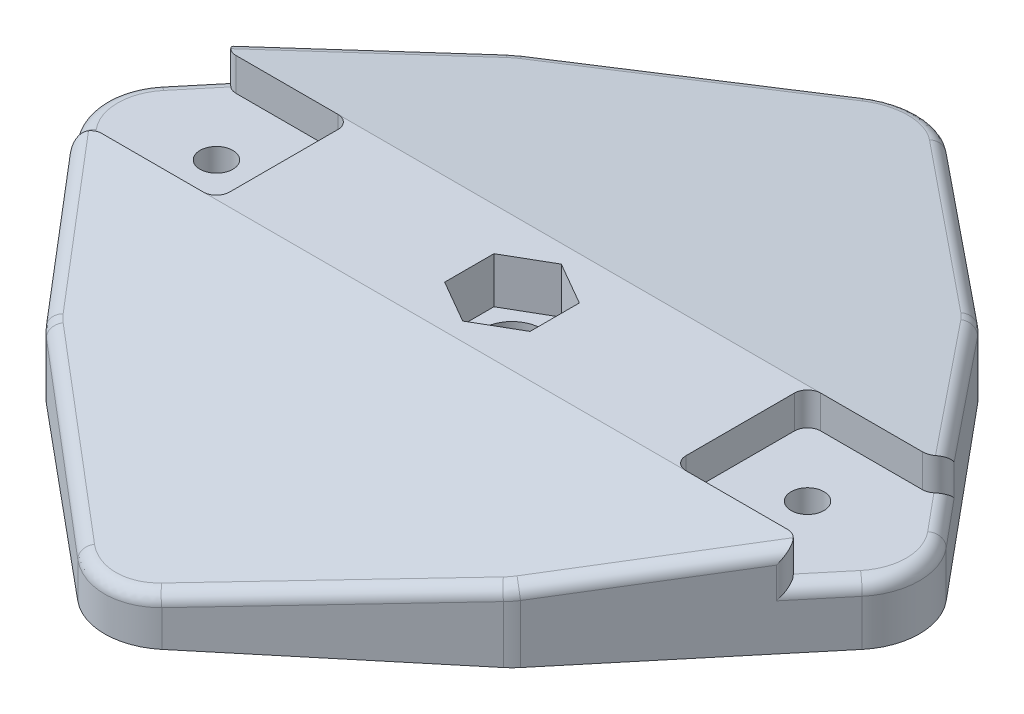
SolidWorks part; units mm, degrees
ref_plane "Front" through (0, 0, 0) normal (0, 0, 1) x (1, 0, 0)
ref_plane "Top" through (0, 0, 0) normal (0, 1, 0) x (1, 0, 0)
ref_plane "Right" through (0, 0, 0) normal (1, 0, 0) x (0, 0, -1)
sketch "Esquisse1" plane through (0, 0, 0) normal (0, 1, 0) x (1, 0, 0)
  line L0 (-45, 0) -> (45, 0) construction
  line L5 (-65.0329, 0) -> (0, -78.1935)
  line L6 (-65.0329, 0) -> (0, 78.1935)
  line L7 (0, -78.1935) -> (65.0329, 0)
  line L8 (0, 78.1935) -> (65.0329, 0)
  circle A0 centre (0, 0) radius 4.5
  circle A1 centre (-45, 0) radius 2.5
  circle A2 centre (45, 0) radius 2.5
  point P48 (0, 0)
  dimension "D1" = 9
  dimension "D3" = 5
  dimension "D5" = 100
  dimension "D2" = 100
  dimension "D4" = 90
  dimension "D6" = 100.5
extrude "Boss.-Extru.1" add sketch "Esquisse1" along normal blind 9
sketch "Esquisse2" plane through (0, 9, 0) normal (0, 1, 0) x (1, 0, 0)
  line L0 (0, 65.0329) -> (-78.1935, 0)
  line L1 (-78.1935, 0) -> (0, -65.0329)
  line L2 (0, -65.0329) -> (78.1935, 0)
  line L3 (78.1935, 0) -> (0, 65.0329)
  line L4 (-78.1935, 0) -> (78.1935, 0) construction
  line L5 (65.0329, 0) -> (0, 78.1935) construction
  dimension "D1" = 100.5
extrude "Enlèv. mat.-Extru.1" cut sketch "Esquisse2" against normal through all flip side to cut
fillet "Congé1" radius 10 8 edges at (0, 4.5, 65.0329) (-35.5043, 4.5, 35.5043) (-35.5043, 4.5, -35.5043) (0, 4.5, -65.0329) (35.5043, 4.5, -35.5043) (65.0329, 4.5, 0) (35.5043, 4.5, 35.5043) (-65.0329, 4.5, 0)
sketch "Esquisse3" plane through (0, 9, 0) normal (0, 1, 0) x (1, 0, 0)
  line L0 (0, -50) -> (0, 50) construction
  line L1 (-56.508, 10.25) -> (-34.75, 10.25)
  line L3 (-56.508, -10.25) -> (-34.75, -10.25)
  line L4 (-34.75, 10.25) -> (-34.75, -10.25)
  line L5 (-45, -10.25) -> (-45, 10.25) construction
  line L6 (-62.0263, 0) -> (-34.75, 0) construction
  line L7 (56.508, -10.25) -> (36.0918, -34.7978)
  line L8 (-34.7978, -36.0918) -> (-6.3944, -59.7147)
  line L9 (6.3944, -59.7147) -> (34.7978, -36.0918)
  line L10 (36.0918, -34.7978) -> (59.7147, -6.3944)
  line L11 (59.7147, 6.3944) -> (36.0918, 34.7978)
  line L12 (34.7978, 36.0918) -> (6.3944, 59.7147)
  line L13 (-6.3944, 59.7147) -> (-34.7978, 36.0918)
  line L14 (-36.0918, 34.7978) -> (-59.7147, 6.3944)
  line L15 (-59.7147, -6.3944) -> (-36.0918, -34.7978)
  line L16 (-34.7978, -36.0918) -> (-6.3944, -59.7147)
  line L21 (-6.3944, 59.7147) -> (-34.7978, 36.0918)
  line L22 (-36.0918, 34.7978) -> (-56.508, 10.25)
  line L23 (-56.508, -10.25) -> (-36.0918, -34.7978)
  line L24 (36.0918, 34.7978) -> (56.508, 10.25)
  line L25 (6.3944, 59.7147) -> (34.7978, 36.0918)
  line L26 (34.7978, -36.0918) -> (6.3944, -59.7147)
  line L27 (34.75, 10.25) -> (34.75, -10.25)
  line L28 (56.508, -10.25) -> (34.75, -10.25)
  line L29 (56.508, 10.25) -> (34.75, 10.25)
  circle A0 centre (0, 0) radius 4.5 construction
  circle A1 centre (0, 0) radius 4.5
  circle A3 centre (-45, 0) radius 2.5 construction
  arc A4 (-59.7147, 6.3944) -> (-59.7147, -6.3944) centre (-52.0263, 0) ccw construction
  arc A5 (36.0918, -34.7978) -> (34.7978, -36.0918) centre (28.4034, -28.4034) cw
  arc A6 (34.7978, 36.0918) -> (36.0918, 34.7978) centre (28.4034, 28.4034) cw
  arc A8 (-6.3944, -59.7147) -> (6.3944, -59.7147) centre (0, -52.0263) ccw
  arc A9 (34.7978, -36.0918) -> (36.0918, -34.7978) centre (28.4034, -28.4034) ccw
  arc A10 (59.7147, -6.3944) -> (59.7147, 6.3944) centre (52.0263, 0) ccw
  arc A11 (36.0918, 34.7978) -> (34.7978, 36.0918) centre (28.4034, 28.4034) ccw
  arc A12 (6.3944, 59.7147) -> (-6.3944, 59.7147) centre (0, 52.0263) ccw
  arc A13 (-34.7978, 36.0918) -> (-36.0918, 34.7978) centre (-28.4034, 28.4034) ccw
  arc A14 (-59.7147, 6.3944) -> (-59.7147, -6.3944) centre (-52.0263, 0) ccw
  arc A15 (-36.0918, -34.7978) -> (-34.7978, -36.0918) centre (-28.4034, -28.4034) ccw
  arc A16 (-6.3944, -59.7147) -> (6.3944, -59.7147) centre (0, -52.0263) ccw
  arc A20 (6.3944, 59.7147) -> (-6.3944, 59.7147) centre (0, 52.0263) ccw
  arc A21 (-34.7978, 36.0918) -> (-36.0918, 34.7978) centre (-28.4034, 28.4034) ccw
  arc A23 (-36.0918, -34.7978) -> (-34.7978, -36.0918) centre (-28.4034, -28.4034) ccw
  point P49 (45, 0)
  point P91 (-45, 0)
  dimension "D1" = 0
  dimension "D2" = 20.5
  dimension "D3" = 10.25
extrude "Boss.-Extru.2" add sketch "Esquisse3" along normal blind 5
sketch "Esquisse4" plane through (0, 14, 0) normal (0, 1, 0) x (1, 0, 0)
  line L1 (6.5, 3.7528) -> (0, 7.5056)
  line L2 (0, 7.5056) -> (-6.5, 3.7528)
  line L3 (-6.5, 3.7528) -> (-6.5, -3.7528)
  line L4 (-6.5, -3.7528) -> (0, -7.5056)
  line L5 (0, -7.5056) -> (6.5, -3.7528)
  line L6 (6.5, -3.7528) -> (6.5, 3.7528)
  circle A0 centre (0, 0) radius 6.5 construction
  dimension "D1" = 13
extrude "Enlèv. mat.-Extru.2" cut sketch "Esquisse4" against normal blind 7
sketch "Esquisse5" plane through (0, 0, 0) normal (0, -1, 0) x (1, 0, 0)
  circle A0 centre (-45, 0) radius 6
  circle A1 centre (45, 0) radius 6
  dimension "D1" = 12
extrude "Enlèv. mat.-Extru.3" cut sketch "Esquisse5" against normal blind 4
sketch "Esquisse6" plane through (34.75, 0, 0) normal (1, 0, 0) x (0, 0, -1)
  line L0 (-62.0263, 7) -> (-10.25, 14)
  line L1 (-10.25, 14) -> (10.25, 14)
  line L2 (10.25, 14) -> (62.0263, 7)
  line L4 (-62.0263, 7) -> (-62.0263, 36.4148)
  line L5 (-62.0263, 36.4148) -> (62.0263, 36.4148)
  line L6 (62.0263, 36.4148) -> (62.0263, 7)
  dimension "D1" = 0
  dimension "D2" = 7
  dimension "D3" = 7
extrude "Enlèv. mat.-Extru.5" cut sketch "Esquisse6" against normal through all both and the other way through all
fillet "Congé2" radius 2 28 edges at (-58.1114, 9, -8.3222) (-58.1114, 9, 8.3222) (58.1114, 9, 8.3222) (58.1114, 9, -8.3222) (46.2999, 12.3406, -22.5239) (35.4745, 10.5897, -35.4745) (20.5961, 8.9094, -47.9033) (-46.2999, 12.3406, -22.5239) (-35.4745, 10.5897, -35.4745) (-20.5961, 8.9094, -47.9033) (-46.2999, 12.3406, 22.5239) (-35.4745, 10.5897, 35.4745) (-20.5961, 8.9094, 47.9033) (46.2999, 12.3406, 22.5239) (35.4745, 10.5897, 35.4745) (20.5961, 8.9094, 47.9033) (-62.0263, 9, 0) (62.0263, 9, 0) (-34.75, 11.5, -10.25) (-34.75, 11.5, 10.25) (34.75, 11.5, 10.25) (34.75, 11.5, -10.25) (0, 7, -62.0263) (0, 7, 62.0263) (56.508, 11.5, -10.25) (56.508, 11.5, 10.25) (-56.508, 11.5, -10.25) (-56.508, 11.5, 10.25)
